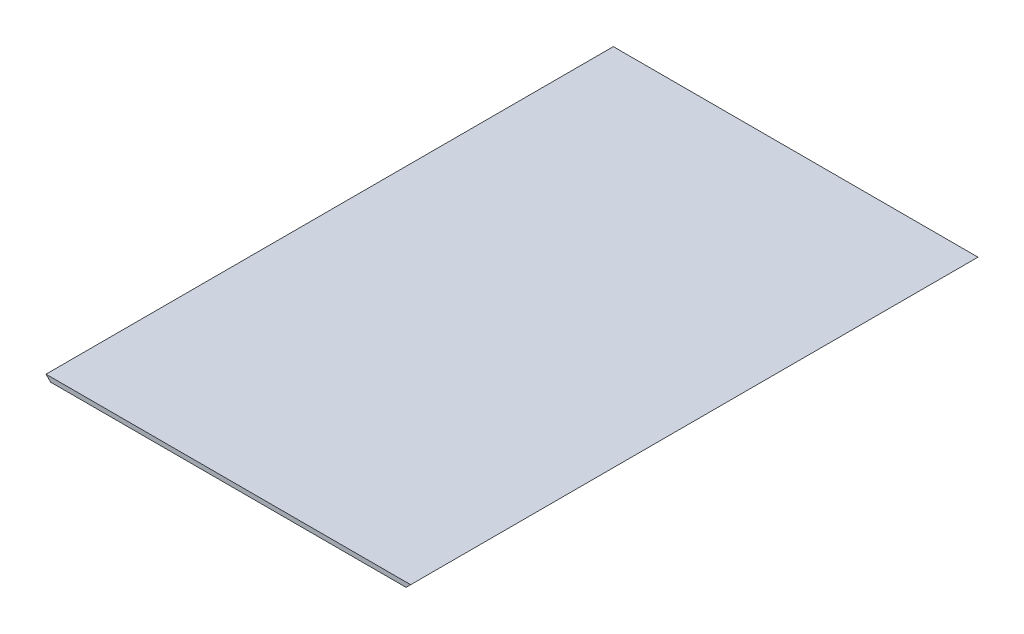
SolidWorks part; units mm, degrees
ref_plane "Front Plane" through (0, 0, 0) normal (0, 0, 1) x (1, 0, 0)
ref_plane "Top Plane" through (0, 0, 0) normal (0, 1, 0) x (1, 0, 0)
ref_plane "Right Plane" through (0, 0, 0) normal (1, 0, 0) x (0, 0, -1)
sketch "Sketch1" plane through (0, 0, 0) normal (0, 1, 0) x (1, 0, 0)
  line L0 (-631, 984.76) -> (631, 984.76)
  line L1 (-631, -984.76) -> (631, -984.76) construction
  line L2 (-631, -984.76) -> (-631, 984.76) construction
  line L3 (-631, 984.76) -> (631, 984.76) construction
  line L4 (631, -984.76) -> (631, 984.76) construction
  line L5 (-631, -984.76) -> (631, 984.76) construction
  line L6 (-631, 984.76) -> (631, -984.76) construction
  line L7 (631, 984.76) -> (631, -984.76)
  line L8 (631, -984.76) -> (-631, -984.76)
  line L9 (-631, -984.76) -> (-631, 984.76)
  point P0 (0, 0)
  dimension "D1" = 1262
  dimension "D2" = 1969.52
extrude "Boss-Extrude1" add sketch "Sketch1" along normal blind 16
sketch "Sketch2" plane through (0, 0, -984.76) normal (0, 0, -1) x (-1, 0, 0)
  line L0 (-631, 16) -> (-615, 0)
  line L1 (-631, 0) -> (631, 0) construction
  line L2 (-615, 0) -> (-631, 0)
  line L3 (-631, 0) -> (-631, 16)
  line L4 (631, 16) -> (615, 0)
  line L5 (615, 0) -> (631, 0)
  line L6 (631, 0) -> (631, 16)
  dimension "D1" = 45
extrude "Cut-Extrude1" cut sketch "Sketch2" against normal through all
ref_plane "Plane1" through (-631, 0, 0) normal (-1, 0, 0) x (0, 0, 1)
sketch "Sketch4" plane through (-631, 0, 0) normal (-1, 0, 0) x (0, 0, 1)
  line L0 (-984.76, 0) -> (-978.6182, 16)
  line L4 (-984.76, 16) -> (984.76, 16) construction
  line L5 (-978.6182, 16) -> (-984.76, 16)
  line L6 (-984.76, 16) -> (-984.76, 0)
  line L7 (984.76, 0) -> (-984.76, 0) construction
  dimension "D1" = 69
extrude "Cut-Extrude3" cut sketch "Sketch4" against normal through all
